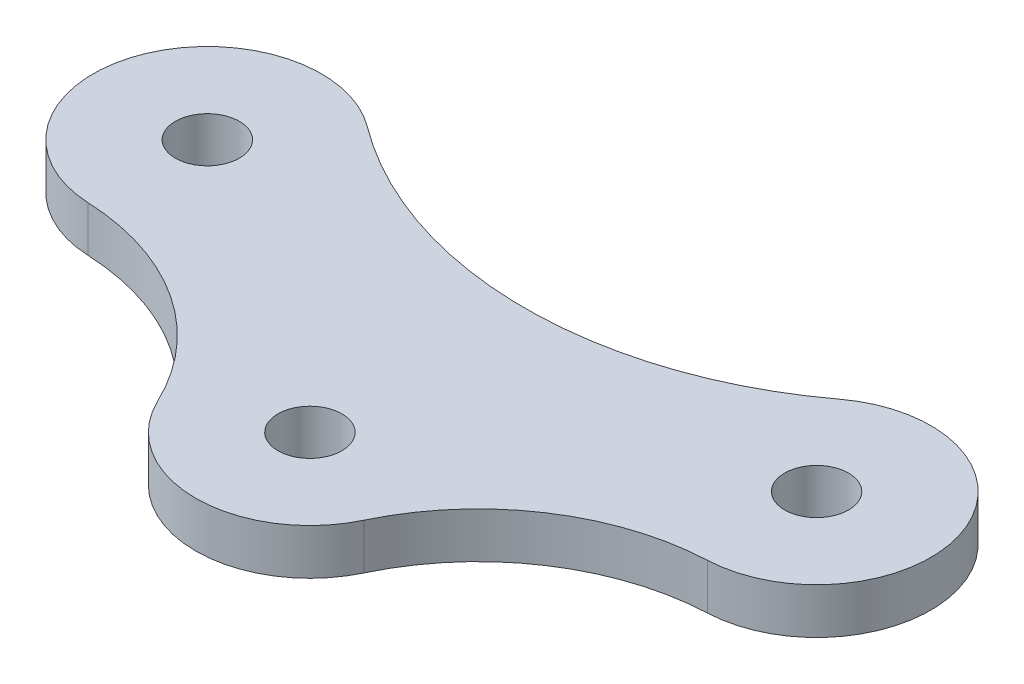
SolidWorks part; units mm, degrees
ref_plane "Front Plane" through (0, 0, 0) normal (0, 0, 1) x (1, 0, 0)
ref_plane "Top Plane" through (0, 0, 0) normal (0, 1, 0) x (1, 0, 0)
ref_plane "Right Plane" through (0, 0, 0) normal (1, 0, 0) x (0, 0, -1)
sketch "Sketch1" plane through (0, 0, 0) normal (0, 1, 0) x (1, 0, 0)
  line L0 (0, 0) -> (0, 68.3748) construction
  circle A0 centre (0, 0) radius 2.1
  circle A1 centre (20, 13.2665) radius 2.1
  circle A2 centre (-20, 13.2665) radius 2.1
  arc A3 (-6.7734, -3.2203) -> (6.7734, -3.2203) centre (0, 0) ccw
  arc A4 (-15.5072, 19.2719) -> (-20.3327, 5.7739) centre (-20, 13.2665) ccw
  arc A5 (20.3327, 5.7739) -> (15.5072, 19.2719) centre (20, 13.2665) ccw
  arc A6 (-15.5072, 19.2719) -> (15.5072, 19.2719) centre (0, 40) ccw
  arc A7 (20.3327, 5.7739) -> (6.7734, -3.2203) centre (21.0332, -10) ccw
  arc A8 (-20.3327, 5.7739) -> (-6.7734, -3.2203) centre (-21.0332, -10) cw
  dimension "D1" = 4.2
  dimension "D2" = 4.2
  dimension "D3" = 4.2
  dimension "D7" = 15
  dimension "D8" = 15
  dimension "D10" = 40
  dimension "D11" = 10
  dimension "D4" = 24
  dimension "D5" = 40
  dimension "D6" = 20
extrude "Boss-Extrude1" add sketch "Sketch1" along normal blind 3
